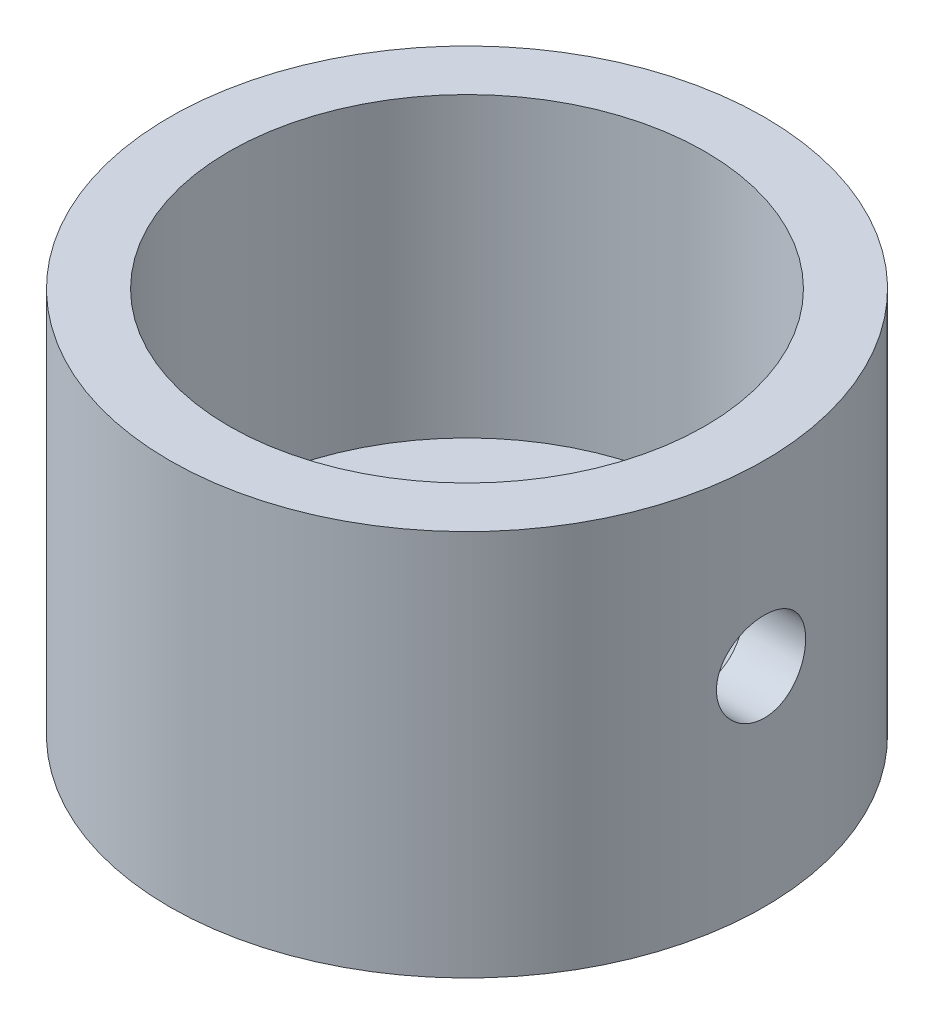
SolidWorks part; units mm, degrees
ref_plane "Front" through (0, 0, 0) normal (0, 0, 1) x (1, 0, 0)
ref_plane "Top" through (0, 0, 0) normal (0, 1, 0) x (1, 0, 0)
ref_plane "Right" through (0, 0, 0) normal (1, 0, 0) x (0, 0, -1)
sketch "Sketch1" plane through (0, 0, 0) normal (0, 1, 0) x (1, 0, 0)
  circle A0 centre (0, 0) radius 10
  dimension "D1" = 20
extrude "Boss-Extrude1" add sketch "Sketch1" along normal blind 3
sketch "Sketch2" plane through (0, 3, 0) normal (0, 1, 0) x (1, 0, 0)
  circle A0 centre (0, 0) radius 1.75
  dimension "D1" = 3.5
extrude "Cut-Extrude1" cut sketch "Sketch2" against normal blind 3
sketch "Sketch3" plane through (0, 3, 0) normal (0, 1, 0) x (1, 0, 0)
  circle A0 centre (0, 0) radius 10
  circle A1 centre (0, 0) radius 8
  dimension "D1" = 2
extrude "Boss-Extrude2" add sketch "Sketch3" along normal blind 10
ref_plane "Plane1" through (10, 0, 0) normal (1, 0, 0) x (0, 0, -1)
sketch "Sketch4" plane through (10, 0, 0) normal (1, 0, 0) x (0, 0, -1)
  line L0 (-10, 0) -> (10, 0) construction
  circle A0 centre (0, 7) radius 1.5
  dimension "D1" = 3
  dimension "D2" = 7
extrude "Cut-Extrude2" cut sketch "Sketch4" against normal blind 5
